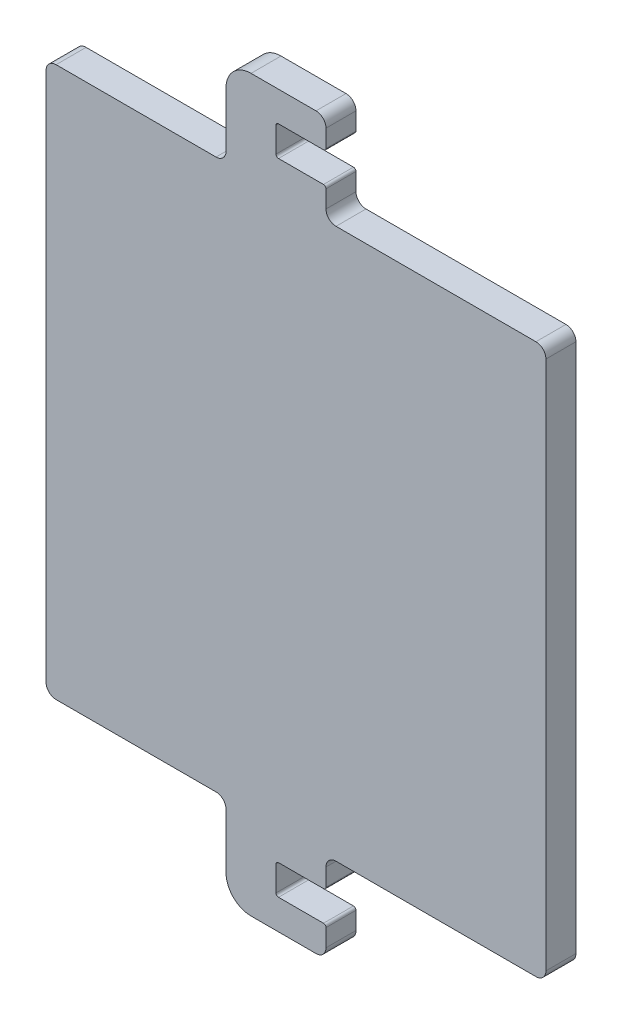
SolidWorks part; units mm, degrees
ref_plane "Alzado" through (0, 0, 0) normal (0, 0, 1) x (1, 0, 0)
ref_plane "Planta" through (0, 0, 0) normal (0, 1, 0) x (1, 0, 0)
ref_plane "Vista lateral" through (0, 0, 0) normal (1, 0, 0) x (0, 0, -1)
sketch "Croquis1" plane through (0, 0, 0) normal (0, 0, 1) x (1, 0, 0)
  line L0 (-9.0425, 0) -> (8.7011, 0) construction
  line L5 (-25, 27.5) -> (25, -27.5) construction
  line L6 (-25, -27.5) -> (25, 27.5) construction
  line L25 (-7, 27.5) -> (-7, 34)
  line L26 (-4.5, 36.5) -> (3, 36.5)
  line L27 (3, 36.5) -> (3, 33.5)
  line L28 (3, 33.5) -> (-2, 33.5)
  line L29 (-2, 33.5) -> (-2, 30.5)
  line L30 (-2, 30.5) -> (3, 30.5)
  line L31 (3, 30.5) -> (3, 27.5)
  line L39 (-25, 27.5) -> (-7, 27.5)
  line L41 (-25, 27.5) -> (-25, -27.5)
  line L43 (25, 27.5) -> (25, -27.5)
  line L44 (-25, 27.5) -> (25, -27.5) construction
  line L45 (-25, -27.5) -> (25, 27.5) construction
  line L46 (3, 27.5) -> (25, 27.5)
  line L47 (3, -27.5) -> (25, -27.5)
  line L48 (3, -30.5) -> (3, -27.5)
  line L49 (-2, -30.5) -> (3, -30.5)
  line L50 (-2, -33.5) -> (-2, -30.5)
  line L51 (3, -33.5) -> (-2, -33.5)
  line L52 (3, -36.5) -> (3, -33.5)
  line L53 (-4.5, -36.5) -> (3, -36.5)
  line L54 (-7, -27.5) -> (-7, -34)
  line L55 (-25, -27.5) -> (-7, -27.5)
  arc A6 (-7, 34) -> (-4.5, 36.5) centre (-4.5, 34) cw
  arc A8 (-7, -34) -> (-4.5, -36.5) centre (-4.5, -34) ccw
  point P0 (0, 0)
  point P8 (-7, 27.5)
  point P19 (8.5, 35.6)
  point P30 (0, 0)
  point P42 (-7, 36.5)
  dimension "D9" = 50
  dimension "D10" = 18
  dimension "D8" = 2.5
  dimension "D1" = 55
  dimension "D2" = 5
  dimension "D3" = 5
  dimension "D4" = 3
  dimension "D5" = 3
  dimension "D6" = 3
  dimension "D7" = 10
  dimension "D11" = 9
extrude "Saliente-Extruir1" add sketch "Croquis1" along normal blind 3 contours L25 A6 L26 L27 L28 L29 L30 L31 L46 L43 L47 L48 L49 L50 L51 L52 L53 A8 L54 L55 L41 L39
fillet "Redondeo1" radius 1 10 edges at (-25, -27.5, 1.5) (25, -27.5, 1.5) (3, -36.5, 1.5) (-25, 27.5, 1.5) (25, 27.5, 1.5) (3, 36.5, 1.5) (-7, -27.5, 1.5) (3, -27.5, 1.5) (3, 27.5, 1.5) (-7, 27.5, 1.5)
fillet "Redondeo2" radius 0.25 8 edges at (-2, -33.5, 1.5) (3, -33.5, 1.5) (-2, -30.5, 1.5) (3, -30.5, 1.5) (3, 33.5, 1.5) (-2, 33.5, 1.5) (-2, 30.5, 1.5) (3, 30.5, 1.5)
